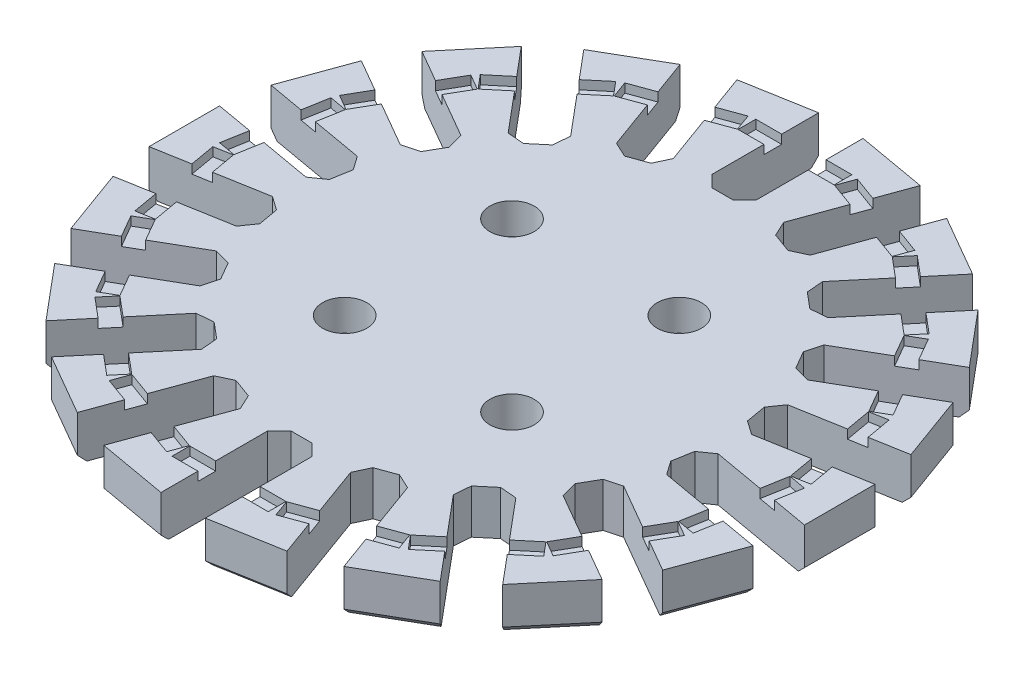
SolidWorks part; units mm, degrees
ref_plane "Front Plane" through (0, 0, 0) normal (0, 0, 1) x (1, 0, 0)
ref_plane "Top Plane" through (0, 0, 0) normal (0, 1, 0) x (1, 0, 0)
ref_plane "Right Plane" through (0, 0, 0) normal (1, 0, 0) x (0, 0, -1)
sketch "Sketch1" plane through (0, 0, 0) normal (0, 1, 0) x (1, 0, 0)
  line L0 (-1.5, 22.2355) -> (-1.5, 14.2355)
  line L1 (-1.5, 22.2355) -> (-6.1955, 21.4076)
  line L2 (-9.0145, 20.3815) -> (-13.1436, 17.9976)
  line L3 (-15.4418, 16.0692) -> (-18.5065, 12.4168)
  line L4 (-20.0065, 9.8187) -> (-21.6372, 5.3384)
  line L5 (-22.1582, 2.3839) -> (-22.1582, -2.3839)
  line L6 (-21.6372, -5.3384) -> (-20.0065, -9.8187)
  line L7 (-18.5065, -12.4168) -> (-15.4418, -16.0692)
  line L8 (-13.1436, -17.9976) -> (-9.0145, -20.3815)
  line L9 (-6.1955, -21.4076) -> (-1.5, -22.2355)
  line L10 (1.5, -22.2355) -> (6.1955, -21.4076)
  line L11 (9.0145, -20.3815) -> (13.1436, -17.9976)
  line L12 (15.4418, -16.0692) -> (18.5065, -12.4168)
  line L13 (20.0065, -9.8187) -> (21.6372, -5.3384)
  line L14 (22.1582, -2.3839) -> (22.1582, 2.3839)
  line L15 (21.6372, 5.3384) -> (20.0065, 9.8187)
  line L16 (18.5065, 12.4168) -> (15.4418, 16.0692)
  line L17 (13.1436, 17.9976) -> (9.0145, 20.3815)
  line L18 (6.1955, 21.4076) -> (1.5, 22.2355)
  line L19 (-1.5, 14.2355) -> (1.5, 14.2355)
  line L20 (1.5, 14.2355) -> (1.5, 22.2355)
  line L21 (6.2784, 12.864) -> (9.0145, 20.3815)
  line L22 (3.4593, 13.89) -> (6.2784, 12.864)
  line L23 (6.1955, 21.4076) -> (3.4593, 13.89)
  line L24 (10.2995, 9.9409) -> (15.4418, 16.0692)
  line L25 (8.0013, 11.8692) -> (10.2995, 9.9409)
  line L26 (13.1436, 17.9976) -> (8.0013, 11.8692)
  line L27 (13.0783, 5.8187) -> (20.0065, 9.8187)
  line L28 (11.5783, 8.4168) -> (13.0783, 5.8187)
  line L29 (18.5065, 12.4168) -> (11.5783, 8.4168)
  line L30 (14.2797, 0.9948) -> (22.1582, 2.3839)
  line L31 (13.7588, 3.9492) -> (14.2797, 0.9948)
  line L32 (21.6372, 5.3384) -> (13.7588, 3.9492)
  line L33 (13.7588, -3.9492) -> (21.6372, -5.3384)
  line L34 (14.2797, -0.9948) -> (13.7588, -3.9492)
  line L35 (22.1582, -2.3839) -> (14.2797, -0.9948)
  line L36 (11.5783, -8.4168) -> (18.5065, -12.4168)
  line L37 (13.0783, -5.8187) -> (11.5783, -8.4168)
  line L38 (20.0065, -9.8187) -> (13.0783, -5.8187)
  line L39 (8.0013, -11.8692) -> (13.1436, -17.9976)
  line L40 (10.2995, -9.9409) -> (8.0013, -11.8692)
  line L41 (15.4418, -16.0692) -> (10.2995, -9.9409)
  line L42 (3.4593, -13.89) -> (6.1955, -21.4076)
  line L43 (6.2784, -12.864) -> (3.4593, -13.89)
  line L44 (9.0145, -20.3815) -> (6.2784, -12.864)
  line L45 (-1.5, -14.2355) -> (-1.5, -22.2355)
  line L46 (1.5, -14.2355) -> (-1.5, -14.2355)
  line L47 (1.5, -22.2355) -> (1.5, -14.2355)
  line L48 (-6.2784, -12.864) -> (-9.0145, -20.3815)
  line L49 (-3.4593, -13.89) -> (-6.2784, -12.864)
  line L50 (-6.1955, -21.4076) -> (-3.4593, -13.89)
  line L51 (-10.2995, -9.9409) -> (-15.4418, -16.0692)
  line L52 (-8.0013, -11.8692) -> (-10.2995, -9.9409)
  line L53 (-13.1436, -17.9976) -> (-8.0013, -11.8692)
  line L54 (-13.0783, -5.8187) -> (-20.0065, -9.8187)
  line L55 (-11.5783, -8.4168) -> (-13.0783, -5.8187)
  line L56 (-18.5065, -12.4168) -> (-11.5783, -8.4168)
  line L57 (-14.2797, -0.9948) -> (-22.1582, -2.3839)
  line L58 (-13.7588, -3.9492) -> (-14.2797, -0.9948)
  line L59 (-21.6372, -5.3384) -> (-13.7588, -3.9492)
  line L60 (-13.7588, 3.9492) -> (-21.6372, 5.3384)
  line L61 (-14.2797, 0.9948) -> (-13.7588, 3.9492)
  line L62 (-22.1582, 2.3839) -> (-14.2797, 0.9948)
  line L63 (-11.5783, 8.4168) -> (-18.5065, 12.4168)
  line L64 (-13.0783, 5.8187) -> (-11.5783, 8.4168)
  line L65 (-20.0065, 9.8187) -> (-13.0783, 5.8187)
  line L66 (-8.0013, 11.8692) -> (-13.1436, 17.9976)
  line L67 (-10.2995, 9.9409) -> (-8.0013, 11.8692)
  line L68 (-15.4418, 16.0692) -> (-10.2995, 9.9409)
  line L69 (-3.4593, 13.89) -> (-6.1955, 21.4076)
  line L70 (-6.2784, 12.864) -> (-3.4593, 13.89)
  line L71 (-9.0145, 20.3815) -> (-6.2784, 12.864)
  arc A0 (6.1516, 21.2871) -> (1.5, 22.1073) centre (0, 0) ccw construction
  arc A1 (13.0613, 17.8994) -> (8.9707, 20.2611) centre (0, 0) ccw construction
  arc A2 (18.3955, 12.3527) -> (15.3594, 15.971) centre (0, 0) ccw construction
  arc A3 (21.511, 5.3161) -> (19.8955, 9.7546) centre (0, 0) ccw construction
  arc A4 (22.032, -2.3617) -> (22.032, 2.3617) centre (0, 0) ccw construction
  arc A5 (19.8955, -9.7546) -> (21.511, -5.3161) centre (0, 0) ccw construction
  arc A6 (-8.9707, 20.2611) -> (-13.0613, 17.8994) centre (0, 0) ccw construction
  arc A7 (-15.3594, 15.971) -> (-18.3955, 12.3527) centre (0, 0) ccw construction
  arc A8 (-19.8955, 9.7546) -> (-21.511, 5.3161) centre (0, 0) ccw construction
  arc A9 (-22.032, 2.3617) -> (-22.032, -2.3617) centre (0, 0) ccw construction
  arc A10 (-21.511, -5.3161) -> (-19.8955, -9.7546) centre (0, 0) ccw construction
  arc A11 (-18.3955, -12.3527) -> (-15.3594, -15.971) centre (0, 0) ccw construction
  arc A12 (-13.0613, -17.8994) -> (-8.9707, -20.2611) centre (0, 0) ccw construction
  arc A13 (-6.1516, -21.2871) -> (-1.5, -22.1073) centre (0, 0) ccw construction
  arc A14 (1.5, -22.1073) -> (6.1516, -21.2871) centre (0, 0) ccw construction
  arc A15 (8.9707, -20.2611) -> (13.0613, -17.8994) centre (0, 0) ccw construction
  arc A16 (15.3594, -15.971) -> (18.3955, -12.3527) centre (0, 0) ccw construction
  arc A17 (-1.5, 22.1073) -> (-6.1516, 21.2871) centre (0, 0) ccw construction
  point P96 (0, 0)
  dimension "D1" = 44.3163
  dimension "D2" = 3
  dimension "D3" = 1.5
  dimension "D4" = 8
  dimension "D5" = 18
extrude "Boss-Extrude1" add sketch "Sketch1" along normal blind 3
chamfer "Chamfer1" distance 0.8 angle 45 36 edges at (-10.2995, 1.5, 9.9409) (-8.0013, 1.5, 11.8692) (-3.4593, 1.5, 13.89) (1.5, 1.5, 14.2355) (6.2784, 1.5, 12.864) (10.2995, 1.5, 9.9409) (13.0783, 1.5, 5.8187) (-6.2784, 1.5, 12.864) (-1.5, 1.5, 14.2355) (3.4593, 1.5, 13.89) (8.0013, 1.5, 11.8692) (11.5783, 1.5, 8.4168) (14.2797, 1.5, 0.9948) (13.7588, 1.5, -3.9492) (11.5783, 1.5, -8.4168) (8.0013, 1.5, -11.8692) (13.7588, 1.5, 3.9492) (14.2797, 1.5, -0.9948) (13.0783, 1.5, -5.8187) (10.2995, 1.5, -9.9409) (3.4593, 1.5, -13.89) (-1.5, 1.5, -14.2355) (-13.0783, 1.5, -5.8187) (-10.2995, 1.5, -9.9409) (-6.2784, 1.5, -12.864) (1.5, 1.5, -14.2355) (-3.4593, 1.5, -13.89) (-8.0013, 1.5, -11.8692) (-11.5783, 1.5, -8.4168) (-14.2797, 1.5, -0.9948) (-13.7588, 1.5, -3.9492) (-13.7588, 1.5, 3.9492) (-14.2797, 1.5, 0.9948) (-11.5783, 1.5, 8.4168) (-13.0783, 1.5, 5.8187) (6.2784, 1.5, -12.864)
sketch "Sketch2" plane through (0, 3, 0) normal (0, 1, 0) x (1, 0, 0)
  line L0 (-3.25, 19.7355) -> (3.25, 19.7355)
  line L2 (3.25, 19.7355) -> (3.25, 18.5355)
  line L3 (3.25, 18.5355) -> (-3.25, 18.5355)
  line L4 (-3.25, 18.5355) -> (-3.25, 19.7355)
  line L5 (3.2855, 18.5292) -> (3.6959, 19.6569)
  line L6 (3.6959, 19.6569) -> (9.8039, 17.4337)
  line L7 (9.8039, 17.4337) -> (9.3935, 16.3061)
  line L8 (9.3935, 16.3061) -> (3.2855, 18.5292)
  line L9 (9.4248, 16.2881) -> (10.1961, 17.2073)
  line L10 (10.1961, 17.2073) -> (15.1754, 13.0292)
  line L11 (15.1754, 13.0292) -> (14.404, 12.11)
  line L12 (14.404, 12.11) -> (9.4248, 16.2881)
  line L13 (14.4272, 12.0823) -> (15.4665, 12.6823)
  line L14 (15.4665, 12.6823) -> (18.7165, 7.0532)
  line L15 (18.7165, 7.0532) -> (17.6772, 6.4532)
  line L16 (17.6772, 6.4532) -> (14.4272, 12.0823)
  line L17 (17.6896, 6.4193) -> (18.8713, 6.6277)
  line L18 (18.8713, 6.6277) -> (20, 0.2264)
  line L19 (20, 0.2264) -> (18.8183, 0.018)
  line L20 (18.8183, 0.018) -> (17.6896, 6.4193)
  line L21 (18.8183, -0.018) -> (20, -0.2264)
  line L22 (20, -0.2264) -> (18.8713, -6.6277)
  line L23 (18.8713, -6.6277) -> (17.6896, -6.4193)
  line L24 (17.6896, -6.4193) -> (18.8183, -0.018)
  line L25 (17.6772, -6.4532) -> (18.7165, -7.0532)
  line L26 (18.7165, -7.0532) -> (15.4665, -12.6823)
  line L27 (15.4665, -12.6823) -> (14.4272, -12.0823)
  line L28 (14.4272, -12.0823) -> (17.6772, -6.4532)
  line L29 (14.404, -12.11) -> (15.1754, -13.0292)
  line L30 (15.1754, -13.0292) -> (10.1961, -17.2073)
  line L31 (10.1961, -17.2073) -> (9.4248, -16.2881)
  line L32 (9.4248, -16.2881) -> (14.404, -12.11)
  line L33 (9.3935, -16.3061) -> (9.8039, -17.4337)
  line L34 (9.8039, -17.4337) -> (3.6959, -19.6569)
  line L35 (3.6959, -19.6569) -> (3.2855, -18.5292)
  line L36 (3.2855, -18.5292) -> (9.3935, -16.3061)
  line L37 (3.25, -18.5355) -> (3.25, -19.7355)
  line L38 (3.25, -19.7355) -> (-3.25, -19.7355)
  line L39 (-3.25, -19.7355) -> (-3.25, -18.5355)
  line L40 (-3.25, -18.5355) -> (3.25, -18.5355)
  line L41 (-3.2855, -18.5292) -> (-3.6959, -19.6569)
  line L42 (-3.6959, -19.6569) -> (-9.8039, -17.4337)
  line L43 (-9.8039, -17.4337) -> (-9.3935, -16.3061)
  line L44 (-9.3935, -16.3061) -> (-3.2855, -18.5292)
  line L45 (-9.4248, -16.2881) -> (-10.1961, -17.2073)
  line L46 (-10.1961, -17.2073) -> (-15.1754, -13.0292)
  line L47 (-15.1754, -13.0292) -> (-14.404, -12.11)
  line L48 (-14.404, -12.11) -> (-9.4248, -16.2881)
  line L49 (-14.4272, -12.0823) -> (-15.4665, -12.6823)
  line L50 (-15.4665, -12.6823) -> (-18.7165, -7.0532)
  line L51 (-18.7165, -7.0532) -> (-17.6772, -6.4532)
  line L52 (-17.6772, -6.4532) -> (-14.4272, -12.0823)
  line L53 (-17.6896, -6.4193) -> (-18.8713, -6.6277)
  line L54 (-18.8713, -6.6277) -> (-20, -0.2264)
  line L55 (-20, -0.2264) -> (-18.8183, -0.018)
  line L56 (-18.8183, -0.018) -> (-17.6896, -6.4193)
  line L57 (-18.8183, 0.018) -> (-20, 0.2264)
  line L58 (-20, 0.2264) -> (-18.8713, 6.6277)
  line L59 (-18.8713, 6.6277) -> (-17.6896, 6.4193)
  line L60 (-17.6896, 6.4193) -> (-18.8183, 0.018)
  line L61 (-17.6772, 6.4532) -> (-18.7165, 7.0532)
  line L62 (-18.7165, 7.0532) -> (-15.4665, 12.6823)
  line L63 (-15.4665, 12.6823) -> (-14.4272, 12.0823)
  line L64 (-14.4272, 12.0823) -> (-17.6772, 6.4532)
  line L65 (-14.404, 12.11) -> (-15.1754, 13.0292)
  line L66 (-15.1754, 13.0292) -> (-10.1961, 17.2073)
  line L67 (-10.1961, 17.2073) -> (-9.4248, 16.2881)
  line L68 (-9.4248, 16.2881) -> (-14.404, 12.11)
  line L69 (-9.3935, 16.3061) -> (-9.8039, 17.4337)
  line L70 (-9.8039, 17.4337) -> (-3.6959, 19.6569)
  line L71 (-3.6959, 19.6569) -> (-3.2855, 18.5292)
  line L72 (-3.2855, 18.5292) -> (-9.3935, 16.3061)
  line L74 (-22.1582, 2.3839) -> (-22.1582, -2.3839) construction
  point P76 (0, 0)
  dimension "D1" = 6.5
  dimension "D2" = 2.5
  dimension "D3" = 3.25
  dimension "D4" = 1.2
  dimension "D7" = 2.1581
  dimension "D5" = 18
chamfer "Chamfer2" distance 0.5 angle 45 18 edges at (-11.0791, 0, 19.1895) (-16.9741, 0, 14.243) (-20.8219, 0, 7.5785) (-22.1582, 0, 0) (-20.8219, 0, -7.5785) (-16.9741, 0, -14.243) (-11.0791, 0, -19.1895) (-3.8477, 0, -21.8215) (3.8477, 0, -21.8215) (11.0791, 0, -19.1895) (16.9741, 0, -14.243) (20.8219, 0, -7.5785) (22.1582, 0, 0) (20.8219, 0, 7.5785) (16.9741, 0, 14.243) (11.0791, 0, 19.1895) (-3.8477, 0, 21.8215) (3.8477, 0, 21.8215)
sketch "Sketch4" plane through (0, 0, 0) normal (0, -1, 0) x (1, 0, 0)
  line L1 (-5.6569, -5.6569) -> (5.6569, -5.6569) construction
  line L2 (-5.6569, -5.6569) -> (-5.6569, 5.6569) construction
  line L3 (-5.6569, 5.6569) -> (5.6569, 5.6569) construction
  line L4 (5.6569, -5.6569) -> (5.6569, 5.6569) construction
  line L5 (-5.6569, -5.6569) -> (5.6569, 5.6569) construction
  line L6 (-5.6569, 5.6569) -> (5.6569, -5.6569) construction
  circle A8 centre (-5.6569, 5.6569) radius 1.5
  circle A9 centre (5.6569, 5.6569) radius 1.5
  circle A10 centre (5.6569, -5.6569) radius 1.5
  circle A11 centre (-5.6569, -5.6569) radius 1.5
  point P0 (0, 0)
  dimension "D1" = 16
  dimension "D2" = 3
extrude "Cut-Extrude4" cut sketch "Sketch4" against normal up to surface (3 mm away) up to face at (0, 3, 0)
sketch "Sketch9" plane through (0, 0, 0) normal (0, -1, 0) x (1, 0, 0)
  circle A2 centre (0, 0) radius 11
  dimension "D1" = 22
extrude "Cut-Extrude8" cut sketch "Sketch9" against normal blind 0.9
extrude "Cut-Extrude9" cut sketch "Sketch2" against normal blind 0.6
